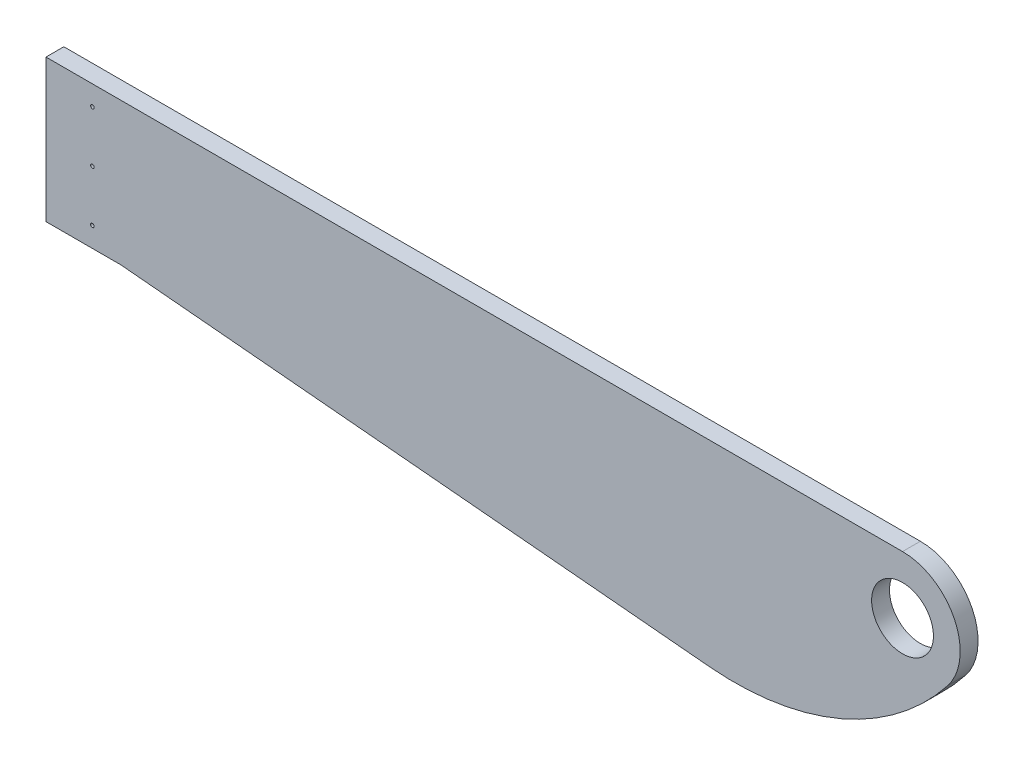
SolidWorks part; units mm, degrees
ref_plane "Front Plane" through (0, 0, 0) normal (0, 0, 1) x (1, 0, 0)
ref_plane "Top Plane" through (0, 0, 0) normal (0, 1, 0) x (1, 0, 0)
ref_plane "Right Plane" through (0, 0, 0) normal (1, 0, 0) x (0, 0, -1)
sketch "Sketch1" plane through (0, 0, 0) normal (0, 0, 1) x (1, 0, 0)
  line L0 (54.2, -30.2131) -> (80.87, -30.2131)
  line L1 (290.3524, 20.525) -> (290.3524, -49.325) construction
  line L2 (54.2, 20.525) -> (359, 20.525)
  line L3 (54.2, -30.2131) -> (54.2, 20.525)
  line L5 (80.87, -30.2131) -> (290.3524, -49.325)
  line L6 (70.71, -23.1321) -> (70.71, -4.8441) construction
  line L7 (70.71, -4.8441) -> (70.71, 13.4439) construction
  line L8 (80.87, -30.2131) -> (80.87, 20.525) construction
  line L9 (60.55, -4.8441) -> (80.87, -4.8441) construction
  line L10 (60.55, 20.525) -> (60.55, -30.2131) construction
  circle A0 centre (359, 0) radius 4 construction
  circle A1 centre (359, 0) radius 11
  arc A2 (375.1721, -12.6388) -> (359, 20.525) centre (359, 0) ccw
  arc A7 (290.3524, -49.325) -> (375.1721, -12.6388) centre (299.1218, 46.7958) ccw
  circle A8 centre (359, 0) radius 20.525 construction
  circle A9 centre (70.71, -4.8441) radius 0.635 construction
  circle A10 centre (70.71, -23.1321) radius 0.635 construction
  circle A11 centre (70.71, 13.4439) radius 0.635 construction
  point P24 (70.71, -4.8441)
  point P25 (0, 0)
  point P26 (0, 0)
  dimension "D1" = 8
  dimension "D2" = 22
  dimension "D4" = 304.8
  dimension "D7" = 26.67
  dimension "D8" = 96.52
  dimension "D10" = 1.27
  dimension "D5" = 69.85
  dimension "D6" = 50.7381
  dimension "D9" = 18.288
  dimension "D11" = 20.32
  dimension "D3" = 9.525
extrude "Boss-Extrude1" add sketch "Sketch1" along normal blind 6.35
sketch "Sketch2" plane through (0, 0, 0) normal (0, 0, -1) x (-1, 0, 0)
  circle A0 centre (-70.71, -23.1321) radius 0.635 construction
  circle A1 centre (-70.71, -4.8441) radius 0.635 construction
  circle A2 centre (-70.71, 13.4439) radius 0.635 construction
  circle A3 centre (-70.71, -23.1321) radius 0.635
  circle A4 centre (-70.71, -4.8441) radius 0.635
  circle A5 centre (-70.71, 13.4439) radius 0.635
extrude "Cut-Extrude1" cut sketch "Sketch2" against normal through all both and the other way through all
